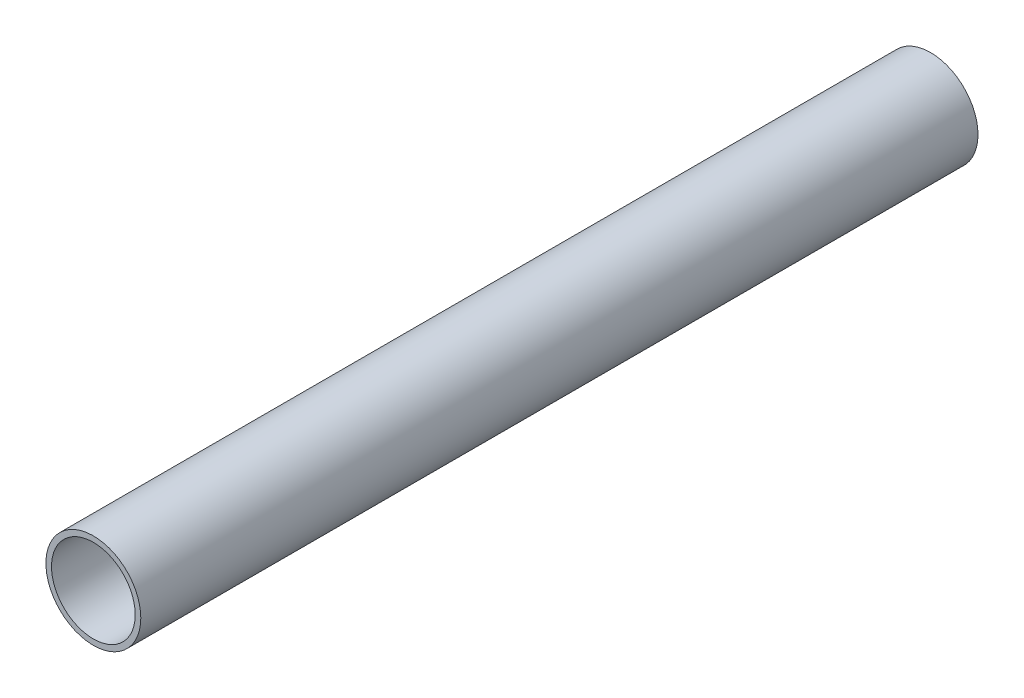
SolidWorks part; units mm, degrees
ref_plane "Front Plane" through (0, 0, 0) normal (0, 0, 1) x (1, 0, 0)
ref_plane "Top Plane" through (0, 0, 0) normal (0, 1, 0) x (1, 0, 0)
ref_plane "Right Plane" through (0, 0, 0) normal (1, 0, 0) x (0, 0, -1)
sketch "Sketch1" plane through (0, 0, 0) normal (0, 0, 1) x (1, 0, 0)
  circle A0 centre (0, 0) radius 15
  circle A1 centre (0, 0) radius 17
  dimension "D1" = 30
  dimension "D2" = 2
extrude "Boss-Extrude1" add sketch "Sketch1" along normal mid plane 300 contours A1 A0
